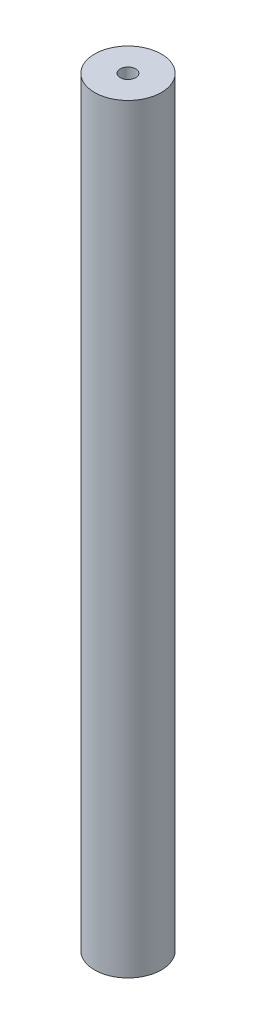
SolidWorks part; units mm, degrees
ref_plane "Front Plane" through (0, 0, 0) normal (0, 0, 1) x (1, 0, 0)
ref_plane "Top Plane" through (0, 0, 0) normal (0, 1, 0) x (1, 0, 0)
ref_plane "Right Plane" through (0, 0, 0) normal (1, 0, 0) x (0, 0, -1)
sketch "Sketch1" plane through (0, 0, 0) normal (0, 1, 0) x (1, 0, 0)
  circle A0 centre (0, 0) radius 6.5
extrude "Boss-Extrude1" add sketch "Sketch1" along normal blind 148
sketch "Sketch2" plane through (0, 148, 0) normal (0, 1, 0) x (1, 0, 0)
  circle A0 centre (0, 0) radius 1.5
extrude "Cut-Extrude1" cut sketch "Sketch2" against normal blind 5
sketch "Sketch4" plane through (0, 0, 0) normal (0, 0, 1) x (1, 0, 0)
  line L0 (0, 142.3332) -> (0, 174.0208) construction
pattern_linear "LPattern1" count 2 spacing 143 along (0, -1, 0) of "Cut-Extrude1"
